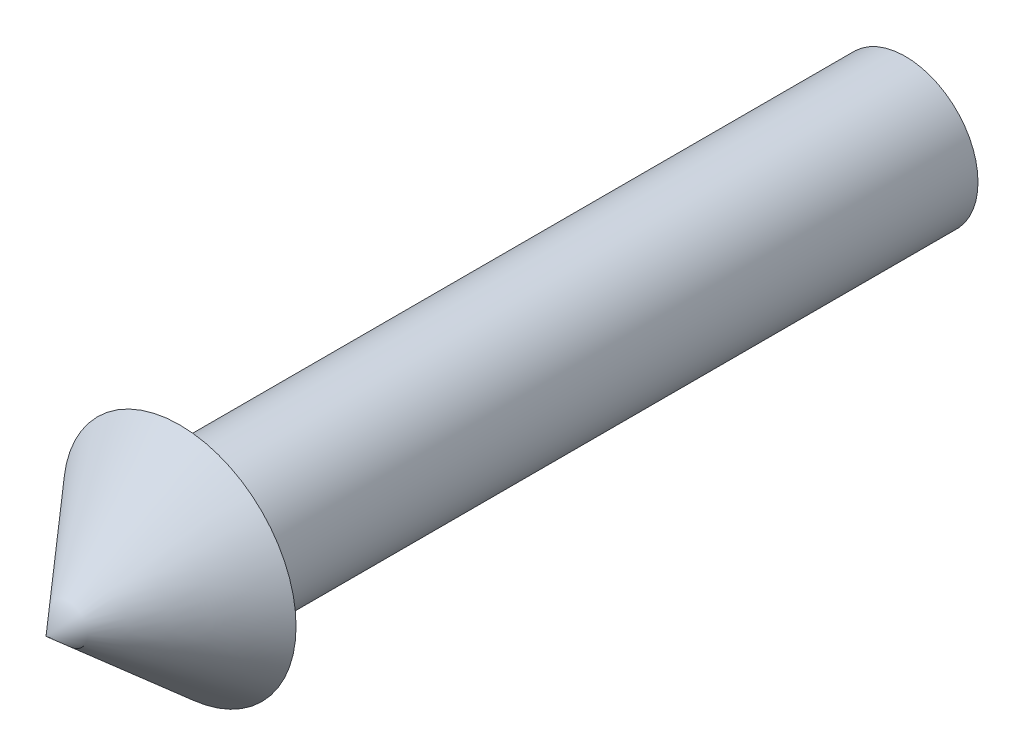
SolidWorks part; units mm, degrees
ref_plane "前视基准面" through (0, 0, 0) normal (0, 0, 1) x (1, 0, 0)
ref_plane "上视基准面" through (0, 0, 0) normal (0, 1, 0) x (1, 0, 0)
ref_plane "右视基准面" through (0, 0, 0) normal (1, 0, 0) x (0, 0, -1)
sketch "草图1" plane through (0, 0, 0) normal (0, 0, 1) x (1, 0, 0)
  circle A0 centre (0, 0) radius 20
  dimension "D1" = 40
extrude "凸台-拉伸1" add sketch "草图1" along normal blind 200
sketch "草图3" plane through (0, 0, 0) normal (1, 0, 0) x (0, 0, -1)
  line L0 (-200, 32.0568) -> (-200, 0)
  line L1 (-200, 20) -> (-200, -20) construction
  line L2 (-200, 0) -> (-236.8602, 0)
  line L3 (-236.8602, 0) -> (-200, 32.0568)
revolve "旋转1" add sketch "草图3" angle 360 about L2
